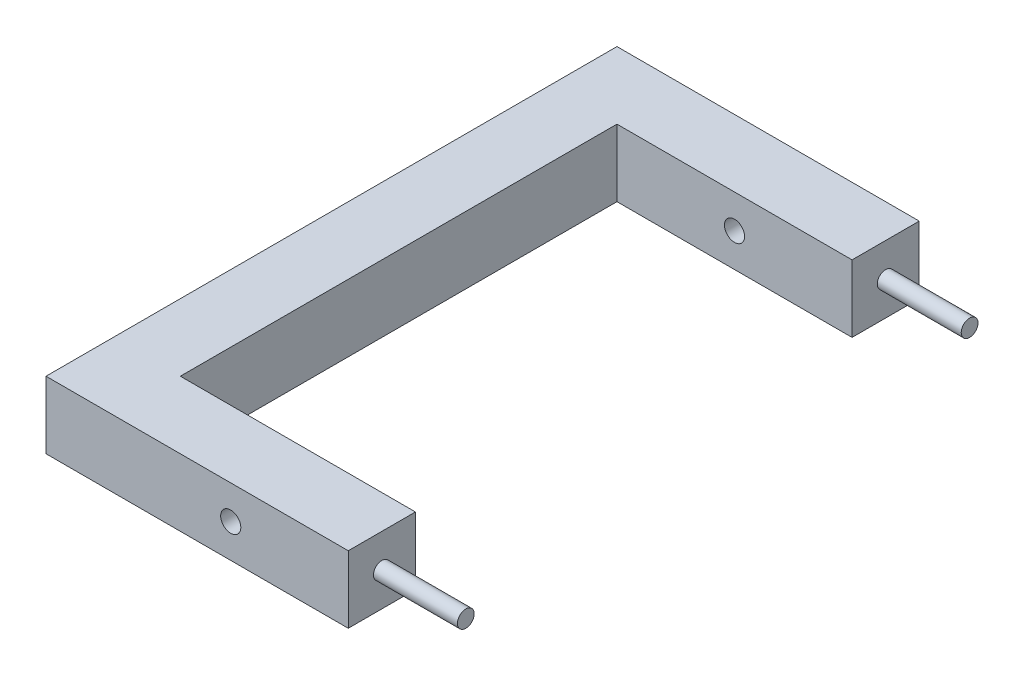
SolidWorks part; units mm, degrees
ref_plane "Front Plane" through (0, 0, 0) normal (0, 0, 1) x (1, 0, 0)
ref_plane "Top Plane" through (0, 0, 0) normal (0, 1, 0) x (1, 0, 0)
ref_plane "Right Plane" through (0, 0, 0) normal (1, 0, 0) x (0, 0, -1)
sketch "Sketch1" plane through (0, 0, 0) normal (0, 1, 0) x (1, 0, 0)
  line L0 (0, 170) -> (0, -194.0717) construction
  line L1 (-287.8827, 0) -> (277.329, 0) construction
  line L2 (0, 170) -> (180, 170)
  line L3 (180, 170) -> (180, 130)
  line L4 (180, 130) -> (40, 130)
  line L5 (40, 130) -> (40, -130)
  line L6 (0, 170) -> (0, -170)
  line L7 (180, -130) -> (40, -130)
  line L8 (180, -170) -> (180, -130)
  line L9 (0, -170) -> (180, -170)
  point P12 (0, 0)
  point P13 (40, 0)
  point P15 (0, 0)
  dimension "D1" = 170
  dimension "D2" = 180
  dimension "D3" = 40
  dimension "D4" = 40
extrude "Boss-Extrude1" add sketch "Sketch1" along normal blind 40
sketch "Sketch2" plane through (0, 0, 170) normal (0, 0, 1) x (1, 0, 0)
  line L0 (180, 40) -> (180, 0) construction
  line L1 (0, 0) -> (180, 0) construction
  circle A0 centre (110, 20) radius 6
  point P6 (173.1049, 18.3354)
  dimension "D1" = 12
  dimension "D2" = 70
  dimension "D3" = 20
extrude "Cut-Extrude1" cut sketch "Sketch2" against normal blind 395
sketch "Sketch3" plane through (180, 0, 0) normal (1, 0, 0) x (0, 0, -1)
  line L0 (-170, 0) -> (-130, 0) construction
  line L2 (-130, 40) -> (-130, 0) construction
  line L3 (0, 22) -> (0, -22) construction
  circle A0 centre (-150, 20) radius 5
  circle A2 centre (150, 20) radius 5
  point P8 (-169.5589, 76.6779)
  dimension "D3" = 10
  dimension "D1" = 20
  dimension "D2" = 20
extrude "Boss-Extrude2" add sketch "Sketch3" along normal blind 50
